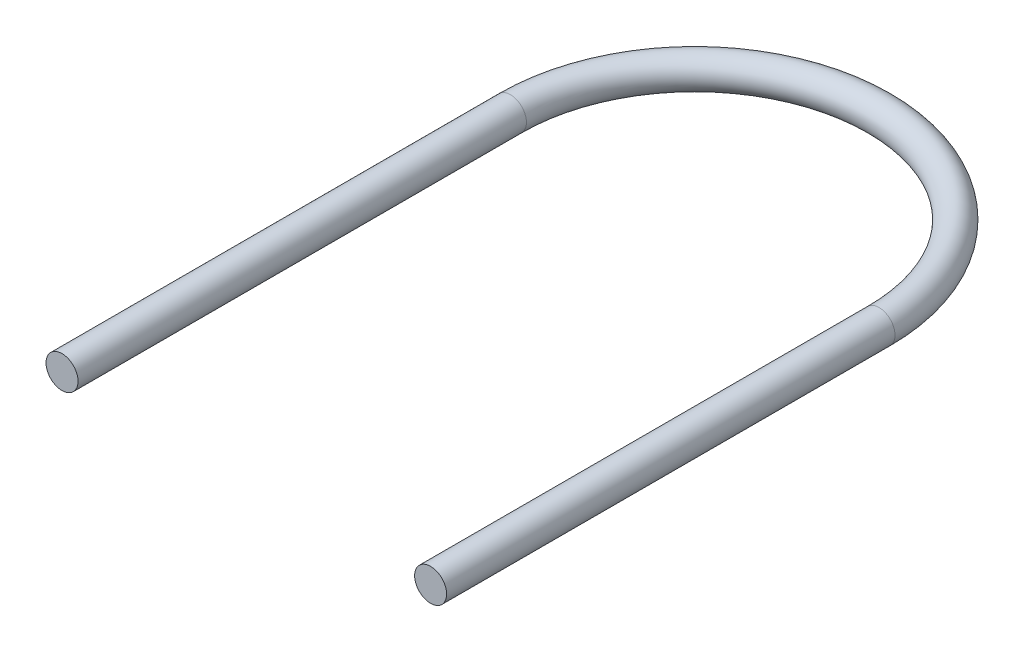
SolidWorks part; units mm, degrees
ref_plane "Front Plane" through (0, 0, 0) normal (0, 0, 1) x (1, 0, 0)
ref_plane "Top Plane" through (0, 0, 0) normal (0, 1, 0) x (1, 0, 0)
ref_plane "Right Plane" through (0, 0, 0) normal (1, 0, 0) x (0, 0, -1)
sketch "Sketch1" plane through (0, 0, 0) normal (0, 1, 0) x (1, 0, 0)
  line L0 (-34.7726, 0) -> (-34.7726, -84.6074)
  line L1 (34.7726, 0) -> (34.7726, -84.6074)
  arc A1 (34.7726, 0) -> (-34.7726, 0) centre (0, 0) ccw
  point P1 (0, 34.7726)
  dimension "D1" = 69.5452
  dimension "D2" = 119.38
ref_plane "Plane2" through (0, 0, 84.6074) normal (0, 0, 1) x (1, 0, 0)
sketch "Sketch6" plane through (0, 0, 84.6074) normal (0, 0, 1) x (1, 0, 0)
  circle A0 centre (34.7726, 0) radius 3.0226
  dimension "D1" = 6.0452
sweep "Sweep2" add profiles "Sketch6" path "Sketch1"
